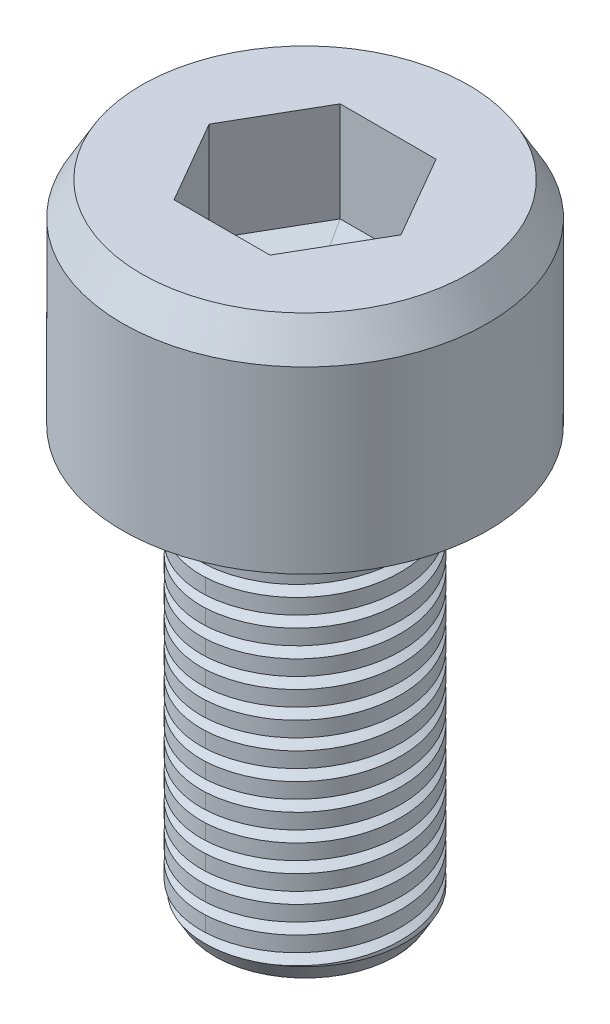
SolidWorks part; units mm, degrees
ref_plane "Front Plane" through (0, 0, 0) normal (0, 0, 1) x (1, 0, 0)
ref_plane "Top Plane" through (0, 0, 0) normal (0, 1, 0) x (1, 0, 0)
ref_plane "Right Plane" through (0, 0, 0) normal (1, 0, 0) x (0, 0, -1)
sketch "Sketch1" plane through (0, 0, 0) normal (0, 1, 0) x (1, 0, 0)
  circle A0 centre (0, 0) radius 2.75
extrude "Boss-Extrude1" add sketch "Sketch1" along normal blind 2.7
sketch "Sketch2" plane through (0, 2.7, 0) normal (0, 1, 0) x (1, 0, 0)
  circle A0 centre (0, 0) radius 2.75
extrude "Boss-Extrude2" add sketch "Sketch2" along normal blind 0.5 draft 30
sketch "Sketch5" plane through (0, 3.2, 0) normal (0, 1, 0) x (1, 0, 0)
  line L1 (1.4434, 0) -> (0.7217, 1.25)
  line L2 (0.7217, 1.25) -> (-0.7217, 1.25)
  line L3 (-0.7217, 1.25) -> (-1.4434, 0)
  line L4 (-1.4434, 0) -> (-0.7217, -1.25)
  line L5 (-0.7217, -1.25) -> (0.7217, -1.25)
  line L6 (0.7217, -1.25) -> (1.4434, 0)
  circle A0 centre (0, 0) radius 1.25 construction
extrude "Cut-Extrude3" cut sketch "Sketch5" against normal blind 1.5
sketch "Sketch6" plane through (0, 1.7, 0) normal (0, 1, 0) x (1, 0, 0)
  line L1 (1.4434, 0) -> (0.7217, 1.25)
  line L2 (0.7217, 1.25) -> (-0.7217, 1.25)
  line L3 (-0.7217, 1.25) -> (-1.4434, 0)
  line L4 (-1.4434, 0) -> (-0.7217, -1.25)
  line L5 (-0.7217, -1.25) -> (0.7217, -1.25)
  line L6 (0.7217, -1.25) -> (1.4434, 0)
  circle A0 centre (0, 0) radius 1.25 construction
extrude "Cut-Extrude4" cut sketch "Sketch6" against normal blind 0.25 draft 80
sketch "Sketch7" plane through (0, 0, 0) normal (0, -1, 0) x (1, 0, 0)
  circle A0 centre (0, 0) radius 1.5
extrude "Boss-Extrude3" add sketch "Sketch7" along normal blind 6
sketch "Sketch8" plane through (0, -6, 0) normal (0, -1, 0) x (1, 0, 0)
  circle A0 centre (0, 0) radius 1.5
extrude "Boss-Extrude4" add sketch "Sketch8" along normal blind 0.25 draft 30
sketch "Sketch9" plane through (0, -6.25, 0) normal (0, -1, 0) x (1, 0, 0)
  circle A0 centre (0, 0) radius 1.5
curve "Helix/Spiral1" pitch 0.4 height 6 turns 15
sketch3d "3DSketch2"
  line L0 (1.6472, -6.42, 0) -> (1.6472, -6.08, 0)
  line L1 (1.6472, -6.08, 0) -> (1.3528, -6.25, 0)
  line L2 (1.3528, -6.25, 0) -> (1.6472, -6.42, 0)
sweep "Cut-Sweep1" cut profiles "3DSketch2" path "Helix/Spiral1"
